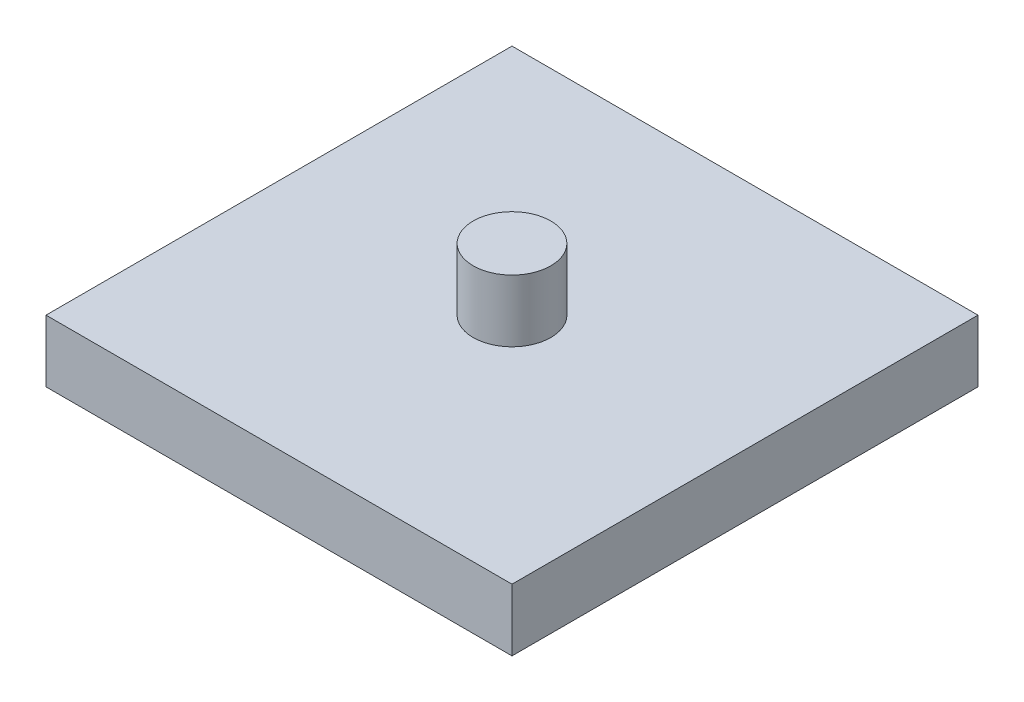
SolidWorks part; units mm, degrees
ref_plane "Front Plane" through (0, 0, 0) normal (0, 0, 1) x (1, 0, 0)
ref_plane "Top Plane" through (0, 0, 0) normal (0, 1, 0) x (1, 0, 0)
ref_plane "Right Plane" through (0, 0, 0) normal (1, 0, 0) x (0, 0, -1)
sketch "Sketch2" plane through (0, 0, 0) normal (0, 1, 0) x (1, 0, 0)
  line L1 (-150, 150) -> (150, 150)
  line L2 (-150, 150) -> (-150, -150)
  line L3 (-150, -150) -> (150, -150)
  line L4 (150, 150) -> (150, -150)
  line L5 (-150, 150) -> (150, -150) construction
  line L6 (-150, -150) -> (150, 150) construction
  point P0 (0, 0)
  dimension "D1" = 300
  dimension "D2" = 300
extrude "Boss-Extrude1" add sketch "Sketch2" along normal blind 40
sketch "Sketch3" plane through (0, 40, 0) normal (0, 1, 0) x (1, 0, 0)
  circle A0 centre (0, 0) radius 25
  dimension "D1" = 50
extrude "Boss-Extrude2" add sketch "Sketch3" along normal blind 40
